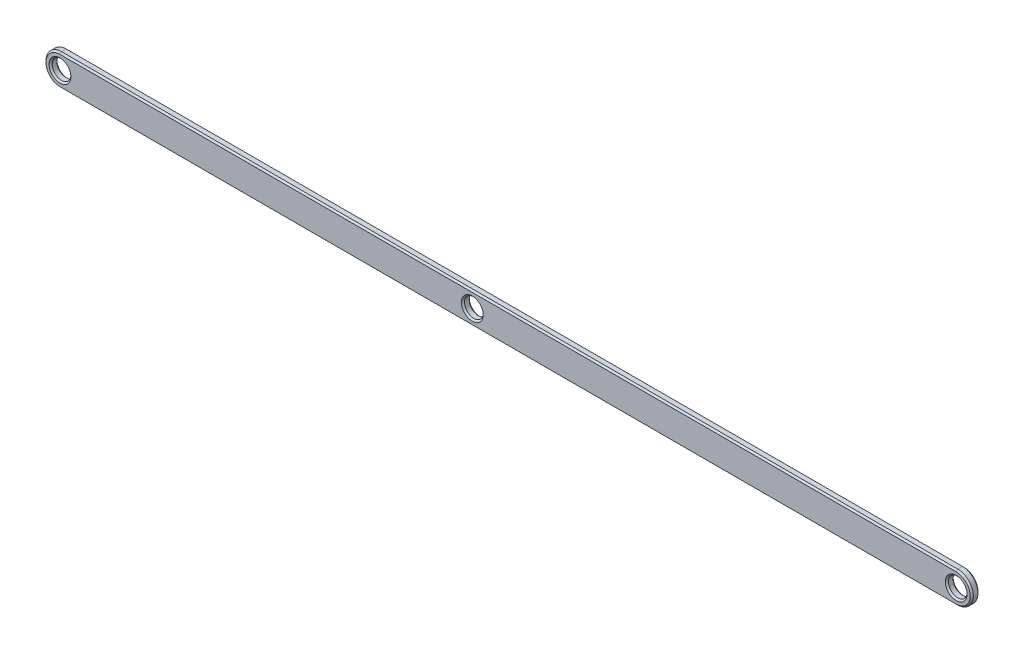
SolidWorks part; units mm, degrees
ref_plane "Front Plane" through (0, 0, 0) normal (0, 0, 1) x (1, 0, 0)
ref_plane "Top Plane" through (0, 0, 0) normal (0, 1, 0) x (1, 0, 0)
ref_plane "Right Plane" through (0, 0, 0) normal (1, 0, 0) x (0, 0, -1)
sketch "Sketch1" plane through (0, 0, 0) normal (0, 0, 1) x (1, 0, 0)
  line L0 (0, 157.4916) -> (0, -223.2358) construction
  line L1 (1440, -50) -> (-1440, -50)
  line L3 (1440, 50) -> (-1440, 50)
  line L4 (-1440, 0) -> (1440, 0) construction
  arc A0 (-1440, 50) -> (-1440, -50) centre (-1440, 0) ccw
  circle A1 centre (-1440, 0) radius 30
  arc A2 (1440, 50) -> (1440, -50) centre (1440, 0) cw
  circle A3 centre (1440, 0) radius 30
  circle A4 centre (-115, 0) radius 30
  point P0 (0, 0)
  dimension "D1" = 60
  dimension "D4" = 60
  dimension "D2" = 20
  dimension "D3" = 2880
  dimension "D5" = 1325
extrude "Boss-Extrude1" add sketch "Sketch1" along normal blind 25
chamfer "Chamfer1" distance 5 angle 45 14 edges at (1410, 0, 0) (-1410, 0, 0) (0, -50, 0) (1490, 0, 0) (0, 50, 0) (-1490, 0, 0) (1410, 0, 25) (0, 50, 25) (1490, 0, 25) (0, -50, 25) (-1490, 0, 25) (-1410, 0, 25) (-85, 0, 0) (-85, 0, 25)
equation "\"length\" = 2880"
equation "\"D3@Sketch1\"=\"length\""
equation "\"D\"= 60"
equation "\"Mid Hole\"= 1325"
equation "\"D5@Sketch1\"=\"Mid Hole\""
